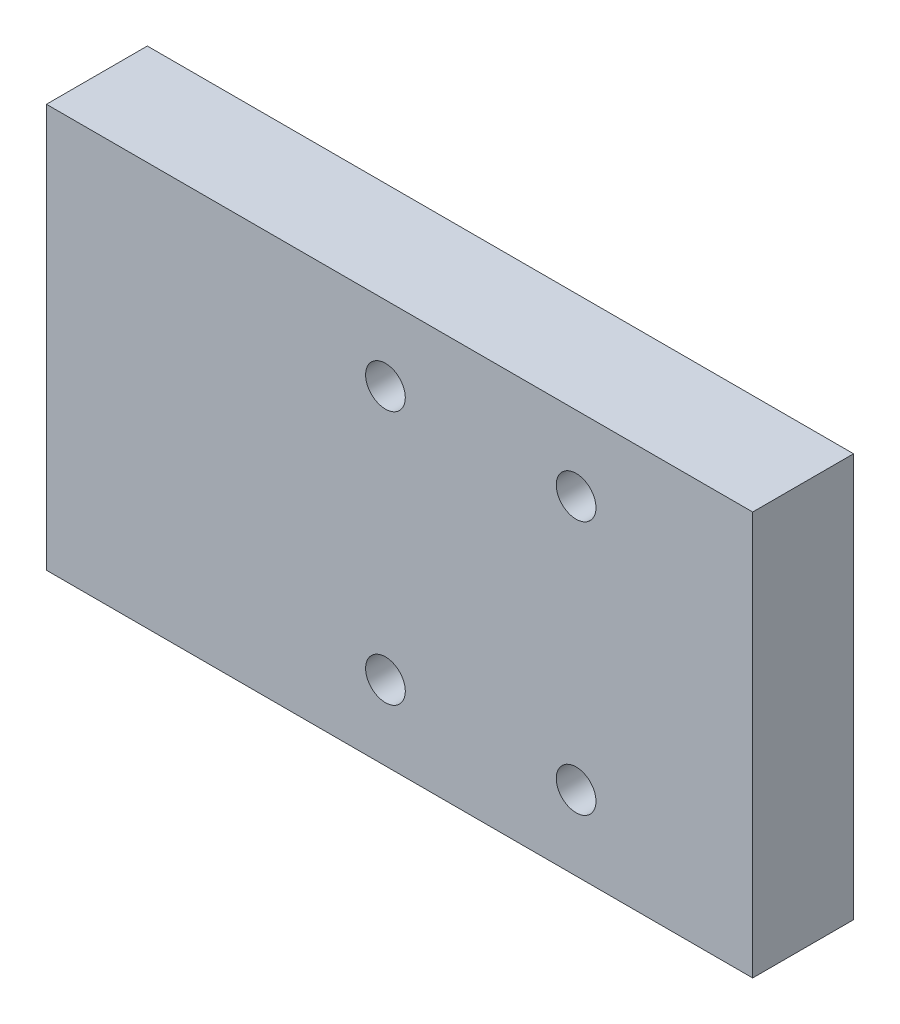
SolidWorks part; units mm, degrees
ref_plane "Plan de face" through (0, 0, 0) normal (0, 0, 1) x (1, 0, 0)
ref_plane "Plan de dessus" through (0, 0, 0) normal (0, 1, 0) x (1, 0, 0)
ref_plane "Plan de droite" through (0, 0, 0) normal (1, 0, 0) x (0, 0, -1)
sketch "Esquisse1" plane through (0, 0, 0) normal (0, 0, 1) x (1, 0, 0)
  line L1 (-22.225, 12.7) -> (22.225, 12.7)
  line L2 (-22.225, 12.7) -> (-22.225, -12.7)
  line L3 (-22.225, -12.7) -> (22.225, -12.7)
  line L4 (22.225, 12.7) -> (22.225, -12.7)
  point P4 (0, 12.7)
  point P6 (22.225, 0)
  point P7 (-22.225, 0)
  dimension "D1" = 44.45
  dimension "D2" = 25.4
extrude "Boss.-Extru.1" add sketch "Esquisse1" along normal mid plane 6.35
sketch "Esquisse2" plane through (0, 0, 3.175) normal (0, 0, 1) x (1, 0, 0)
  line L0 (22.225, -12.7) -> (22.225, 12.7) construction
  circle A0 centre (-0.8875, 8) radius 1.2497
  circle A1 centre (11.1125, 8) radius 1.2497
  dimension "D1" = 12
  dimension "D2" = 8
  dimension "D3" = 2.4994
  dimension "D4" = 11.1125
extrude "Enlèv. mat.-Extru.1" cut sketch "Esquisse2" against normal through all
mirror "Symétrie1" about plane through (0, 0, 0) normal (0, 1, 0) of "Enlèv. mat.-Extru.1"
